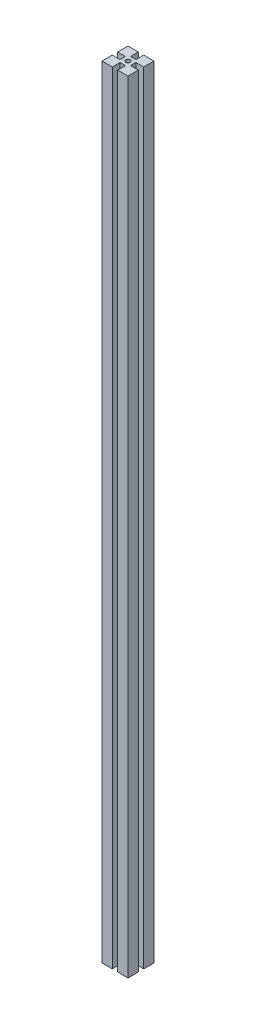
SolidWorks part; units mm, degrees
ref_plane "Ebene vorne" through (0, 0, 0) normal (0, 0, 1) x (1, 0, 0)
ref_plane "Ebene oben" through (0, 0, 0) normal (0, 1, 0) x (1, 0, 0)
ref_plane "Ebene rechts" through (0, 0, 0) normal (1, 0, 0) x (0, 0, -1)
sketch "Skizze1" plane through (0, 0, 0) normal (0, 1, 0) x (1, 0, 0)
  line L0 (-4.1, -20) -> (-4.1, -8)
  line L1 (-20, 20) -> (-4.1, 20)
  line L2 (-20, 20) -> (-20, 4.1)
  line L3 (-20, -20) -> (-4.1, -20)
  line L4 (20, 20) -> (20, 4.1)
  line L5 (-20, 20) -> (20, -20) construction
  line L6 (-20, -20) -> (20, 20) construction
  line L7 (-4.1, -8) -> (4.1, -8)
  line L8 (4.1, -8) -> (4.1, -20)
  line L9 (0, 53.9798) -> (0, -29.8049) construction
  line L10 (4.1, -20) -> (20, -20)
  line L11 (-42.3353, 0) -> (35.9872, 0) construction
  line L12 (4.1, 8) -> (4.1, 20)
  line L13 (-4.1, 20) -> (-4.1, 8)
  line L14 (-4.1, 8) -> (4.1, 8)
  line L15 (4.1, 20) -> (20, 20)
  line L16 (-20, 4.1) -> (-8, 4.1)
  line L17 (-8, 4.1) -> (-8, -4.1)
  line L18 (-8, -4.1) -> (-20, -4.1)
  line L19 (-20, -4.1) -> (-20, -20)
  line L20 (8, 4.1) -> (8, -4.1)
  line L21 (8, -4.1) -> (20, -4.1)
  line L22 (20, 4.1) -> (8, 4.1)
  line L23 (20, -4.1) -> (20, -20)
  point P0 (0, 0)
  dimension "D1" = 40
  dimension "D2" = 8.2
  dimension "D3" = 12
  dimension "D4" = 40
  dimension "D5" = 8.2
  dimension "D6" = 12
extrude "Aufsatz-Linear austragen1" add sketch "Skizze1" along normal blind 1200
sketch "Skizze2" plane through (0, 1200, 0) normal (0, 1, 0) x (1, 0, 0)
  circle A0 centre (0, 0) radius 3.45
  dimension "D1" = 6.9
extrude "Schnitt-Linear austragen1" cut sketch "Skizze2" against normal blind 30
